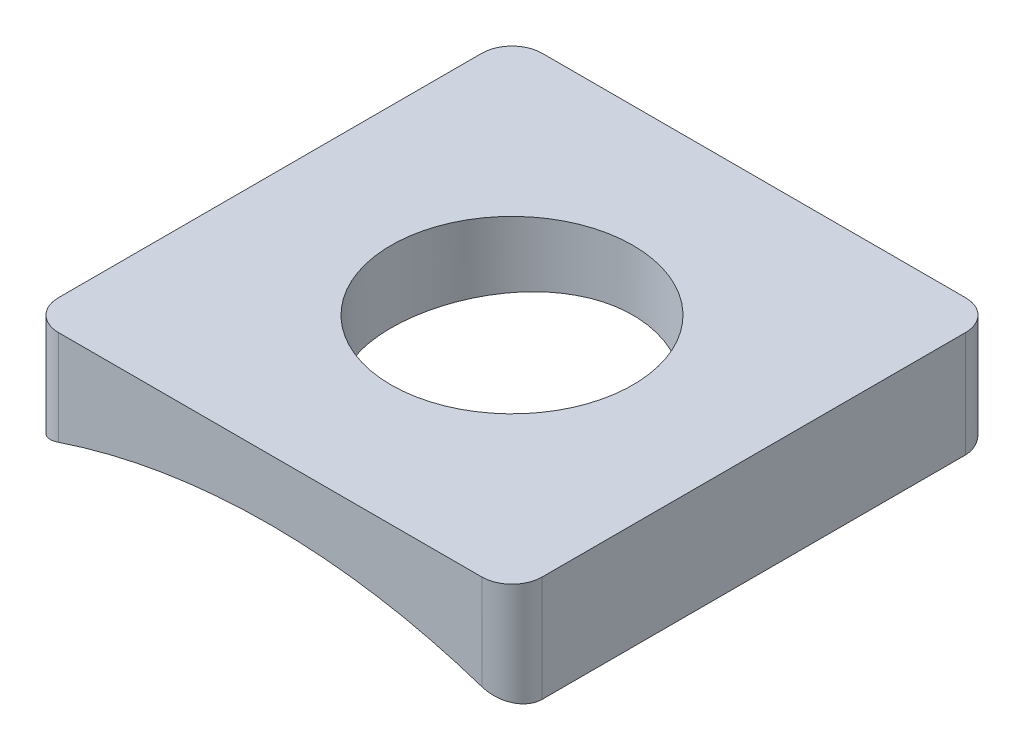
SolidWorks part; units mm, degrees
ref_plane "Płaszczyzna XY" through (0, 0, 0) normal (0, 0, 1) x (1, 0, 0)
ref_plane "Płaszczyzna XZ" through (0, 0, 0) normal (0, 1, 0) x (1, 0, 0)
ref_plane "Płaszczyzna YZ" through (0, 0, 0) normal (1, 0, 0) x (0, 0, -1)
sketch "Szkic1" plane through (0, 0, 0) normal (0, 0, 1) x (1, 0, 0)
  line L0 (0, -0.1235) -> (0, 0.8765)
  line L2 (4, -0.8765) -> (4, 0.8765)
  line L3 (4, 0.8765) -> (-4, 0.8765)
  line L4 (-4, -0.8765) -> (-4, 0.8765)
  line L5 (0.6516, -0.1428) -> (-4, 0.8765) construction
  line L6 (4, 0.8765) -> (-0.6516, -0.1428) construction
  arc A0 (4, -0.8765) -> (-4, -0.8765) centre (0, -11.1235) ccw
  point P0 (0, 0)
  dimension "D2" = 22
  dimension "D1" = 1
  dimension "D3" = 8
extrude "Dodanie-wyciągnięcie1" add sketch "Szkic1" along normal blind 8 contours A0 L2 L3 L0 | A0 L0 L3 L4
sketch "Szkic2" plane through (0, 0.8765, 0) normal (0, 1, 0) x (1, 0, 0)
  line L0 (4, -8) -> (-4, 0) construction
  circle A0 centre (0, -4) radius 2
extrude "Wytnij-wyciągnięcie1" cut sketch "Szkic2" against normal blind 8 contours A0
fillet "Zaokrąglenie1" radius 0.5 4 edges at (4, 0, 8) (4, 0, 0) (-4, 0, 0) (-4, 0, 8)
